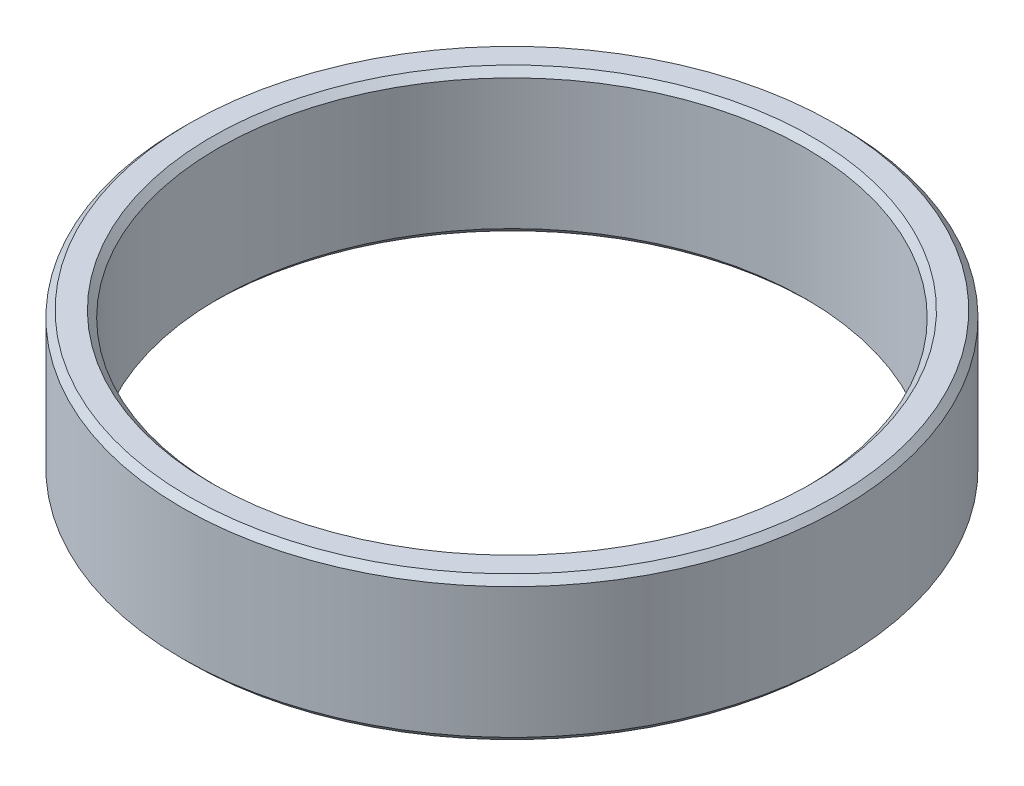
SolidWorks part; units mm, degrees
ref_plane "前视基准面" through (0, 0, 0) normal (0, 0, 1) x (1, 0, 0)
ref_plane "上视基准面" through (0, 0, 0) normal (0, 1, 0) x (1, 0, 0)
ref_plane "右视基准面" through (0, 0, 0) normal (1, 0, 0) x (0, 0, -1)
sketch "草图1" plane through (0, 0, 0) normal (0, 1, 0) x (1, 0, 0)
  circle A0 centre (0, 0) radius 50.5
  circle A1 centre (0, 0) radius 45
  dimension "D1" = 101
  dimension "D2" = 90
extrude "凸台-拉伸1" add sketch "草图1" along normal blind 22
chamfer "倒角1" distance 1 angle 45 4 edges at (0, 0, 45) (0, 22, 45) (0, 0, 50.5) (0, 22, 50.5)
